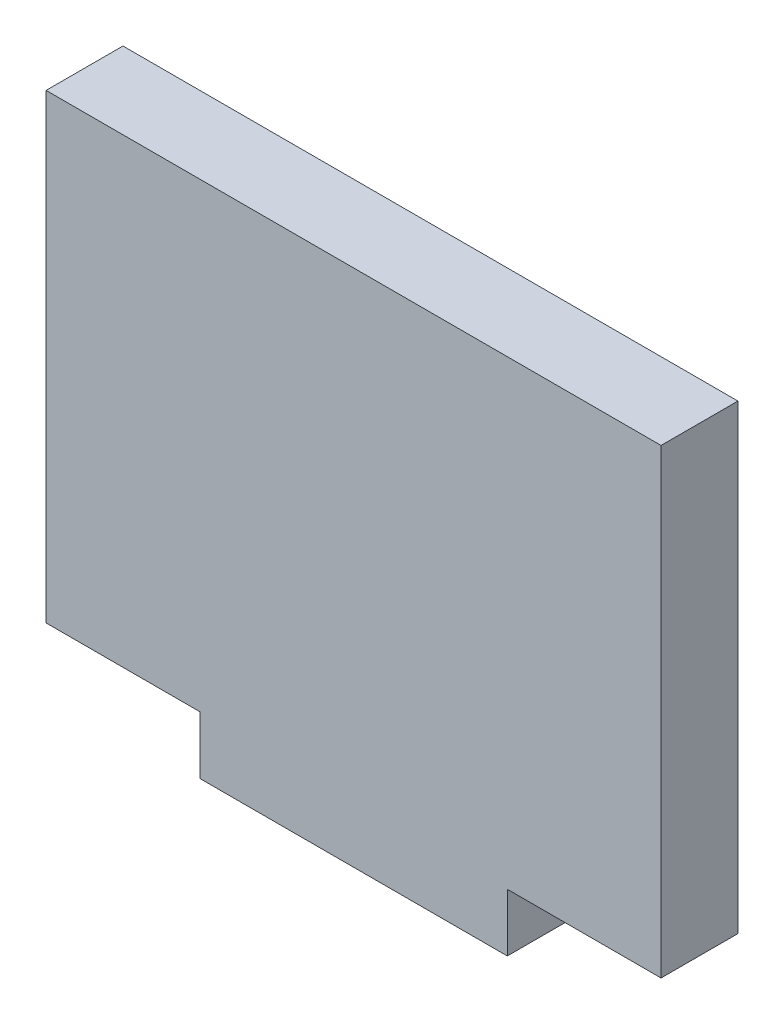
SolidWorks part; units mm, degrees
ref_plane "Front Plane" through (0, 0, 0) normal (0, 0, 1) x (1, 0, 0)
ref_plane "Top Plane" through (0, 0, 0) normal (0, 1, 0) x (1, 0, 0)
ref_plane "Right Plane" through (0, 0, 0) normal (1, 0, 0) x (0, 0, -1)
sketch "Sketch1" plane through (0, 0, 0) normal (0, 0, 1) x (1, 0, 0)
  line L0 (6.35, 0) -> (6.35, -2.3879)
  line L1 (0, 0) -> (6.35, 0)
  line L2 (0, 0) -> (0, 19.05)
  line L3 (0, 19.05) -> (25.4, 19.05)
  line L4 (25.4, 0) -> (25.4, 19.05)
  line L5 (6.35, -2.3879) -> (19.05, -2.3879)
  line L6 (19.05, -2.3879) -> (19.05, 0)
  line L7 (12.7, -2.3879) -> (12.7, 0) construction
  line L8 (19.05, 0) -> (25.4, 0)
  point P11 (0, 0)
  dimension "D1" = 25.4
  dimension "D2" = 19.05
  dimension "D3" = 12.7
extrude "Boss-Extrude1" add sketch "Sketch1" along normal blind 3.175
